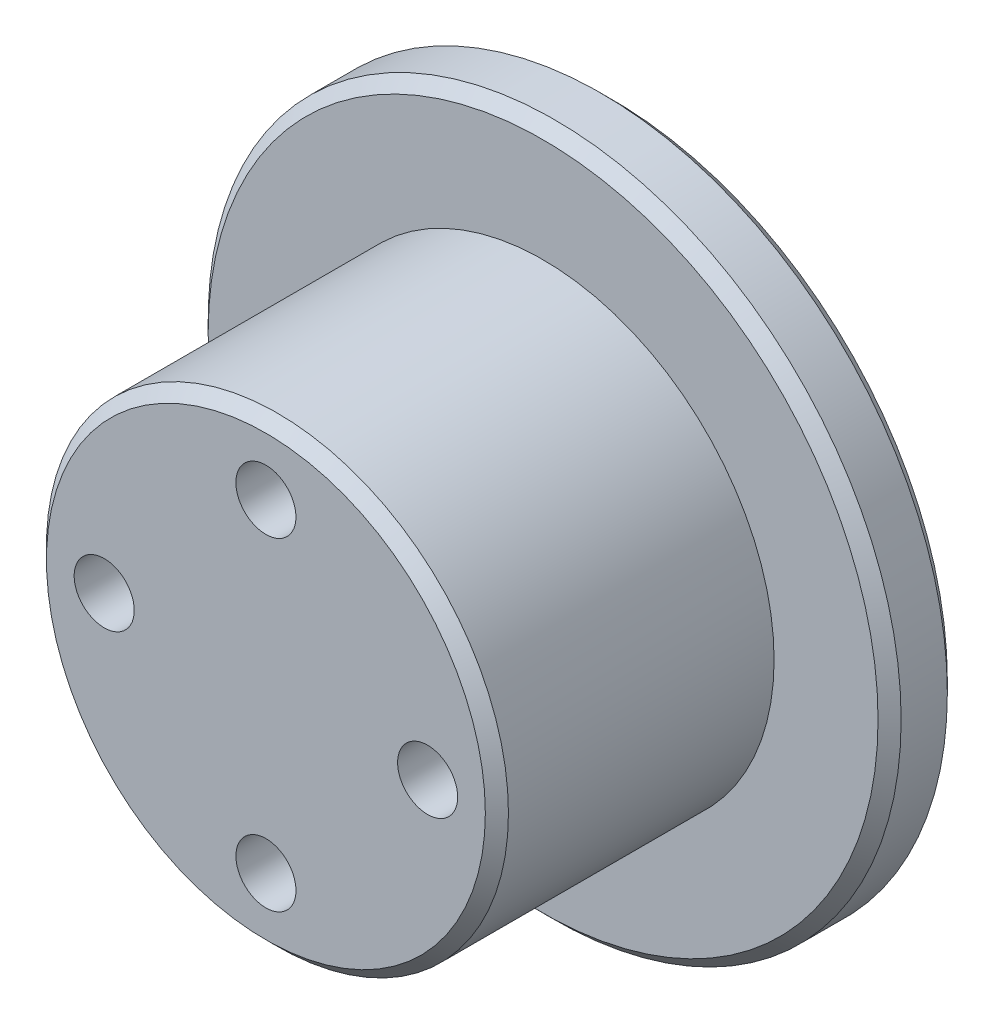
SolidWorks part; units mm, degrees
material "PEI"
ref_plane "前视基准面" through (0, 0, 0) normal (0, 0, 1) x (1, 0, 0)
ref_plane "上视基准面" through (0, 0, 0) normal (0, 1, 0) x (1, 0, 0)
ref_plane "右视基准面" through (0, 0, 0) normal (1, 0, 0) x (0, 0, -1)
other "Configuration Table"
sketch "草图1" plane through (0, 0, 0) normal (0, 0, 1) x (1, 0, 0)
  circle A0 centre (0, 0) radius 15
  dimension "D1" = 30
extrude "凸台-拉伸1" add sketch "草图1" along normal blind 3
sketch "草图2" plane through (0, 0, 3) normal (0, 0, 1) x (1, 0, 0)
  circle A0 centre (0, 0) radius 10
  dimension "D1" = 20
extrude "凸台-拉伸2" add sketch "草图2" along normal blind 12
sketch "草图3" plane through (0, 0, 15) normal (0, 0, 1) x (1, 0, 0)
  circle A0 centre (0, 0) radius 7 construction
  circle A1 centre (0, 7) radius 1.3
  circle A2 centre (0.001, 0.001) radius 7 construction
  circle A3 centre (7.001, 0.001) radius 1.3
  circle A4 centre (0.002, 0) radius 7 construction
  circle A5 centre (0.002, -7) radius 1.3
  circle A6 centre (0.001, -0.001) radius 7 construction
  circle A7 centre (-6.999, -0.001) radius 1.3
  point P20 (0.001, 0)
  dimension "D1" = 14
  dimension "D2" = 2.6
  dimension "D3" = 4
extrude "切除-拉伸1" cut sketch "草图3" against normal blind 6 contours A7 | A1 | A5 | A3
sketch "草图4" plane through (0, 0, 0) normal (0, 0, -1) x (-1, 0, 0)
  circle A0 centre (0, 0) radius 5 construction
  circle A1 centre (0, -5) radius 2
  circle A2 centre (0.0015, 0.0009) radius 5 construction
  circle A3 centre (-4.3286, 2.5009) radius 2
  circle A4 centre (0.0015, -0.0009) radius 5 construction
  circle A5 centre (4.3316, 2.4991) radius 2
  point P15 (0.001, 0)
  dimension "D1" = 10
  dimension "D2" = 4
  dimension "D3" = 3
extrude "切除-拉伸2" cut sketch "草图4" against normal blind 6 contours A1 | A3 | A5
chamfer "倒角1" distance 0.5 angle 45 3 edges at (10, 0, 15) (15, 0, 3) (15, 0, 0)
